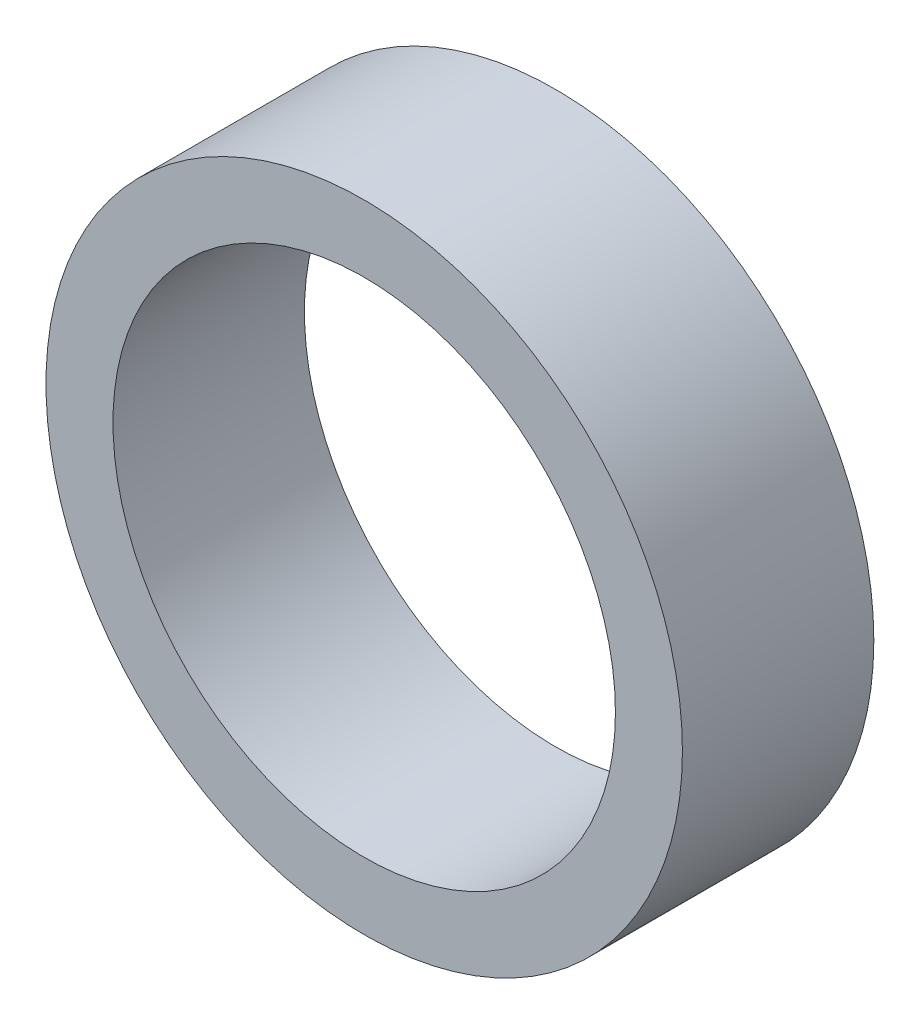
SolidWorks part; units mm, degrees
material "ABS"
ref_plane "Front Plane" through (0, 0, 0) normal (0, 0, 1) x (1, 0, 0)
ref_plane "Top Plane" through (0, 0, 0) normal (0, 1, 0) x (1, 0, 0)
ref_plane "Right Plane" through (0, 0, 0) normal (1, 0, 0) x (0, 0, -1)
sketch "Sketch1" plane through (0, 0, 3) normal (0, 0, 1) x (1, 0, 0)
  circle A0 centre (32.5, 0) radius 3.325
  circle A1 centre (32.5, 0) radius 2.625
  dimension "D1" = 6.65
  dimension "D2" = 5.25
extrude "Boss-Extrude1" add sketch "Sketch1" along normal blind 2 from offset 5
equation "\"RingPinShaft\"= 5.05"
equation "\"CenterBearingOut\"=32.00"
equation "\"OutputBearingOut\"=50.00"
equation "\"RingPostIn\"=5.15"
equation "\"CamBearingOut\"=15.1"
equation "\"DiskOutputShaft\"=10.1"
equation "\"CenterShaft\"=25.2"
equation "\"Eccentricity\"=2"
equation "\"CycCamShaft\"=10.05"
equation "\"m3Thru\"=3.15"
equation "\"m3Insert\"=4.2"
equation "\"D2@Sketch1\"=\"RingPostIn\"+0.1"
equation "\"D1@Sketch1\"=\"RingPostIn\"+1.5"
